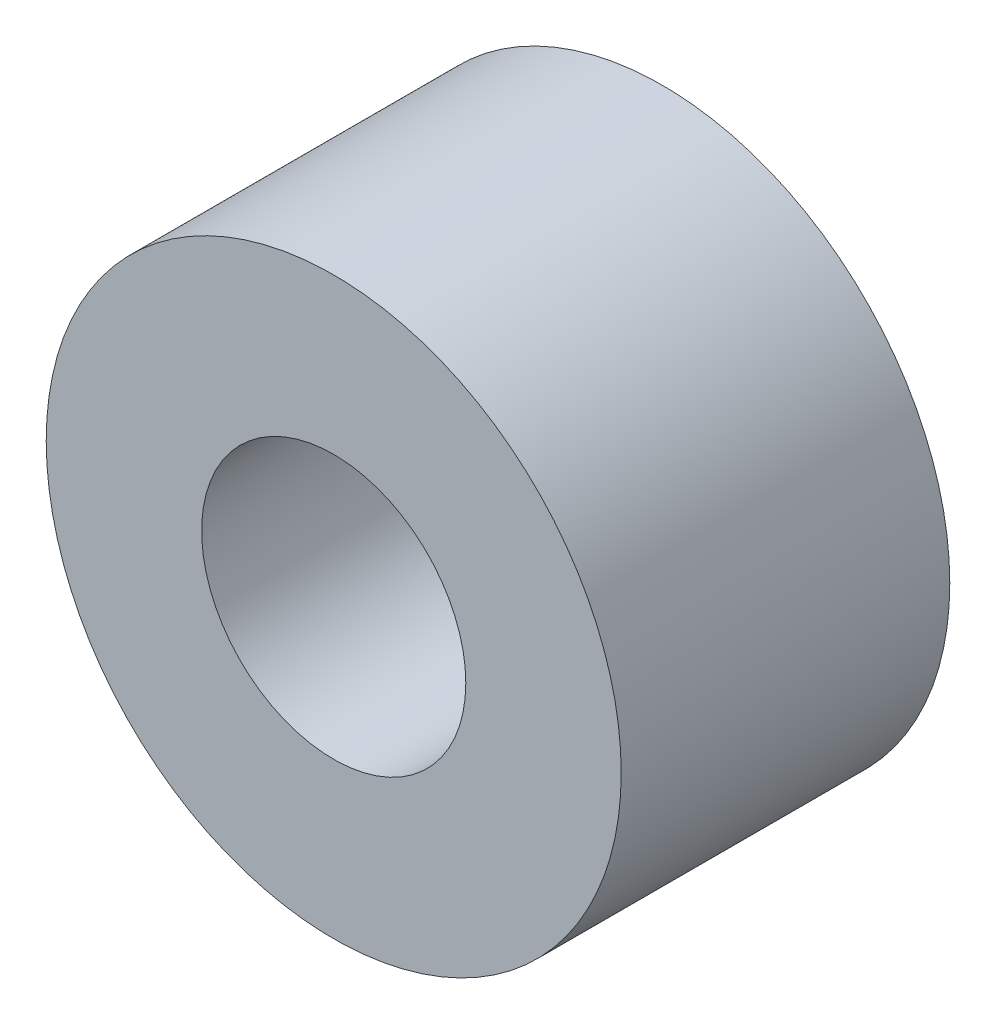
SolidWorks part; units mm, degrees
material "Birch Plywood"
ref_plane "Front Plane" through (0, 0, 0) normal (0, 0, 1) x (1, 0, 0)
ref_plane "Top Plane" through (0, 0, 0) normal (0, 1, 0) x (1, 0, 0)
ref_plane "Right Plane" through (0, 0, 0) normal (1, 0, 0) x (0, 0, -1)
sketch "Sketch1" plane through (0, 0, 0) normal (0, 0, 1) x (1, 0, 0)
  circle A0 centre (0, 0) radius 5.5562
  circle A1 centre (0, 0) radius 2.5527
  dimension "D1" = 5.1054
  dimension "D2" = 11.1125
extrude "Boss-Extrude1" add sketch "Sketch1" along normal blind 6.35
